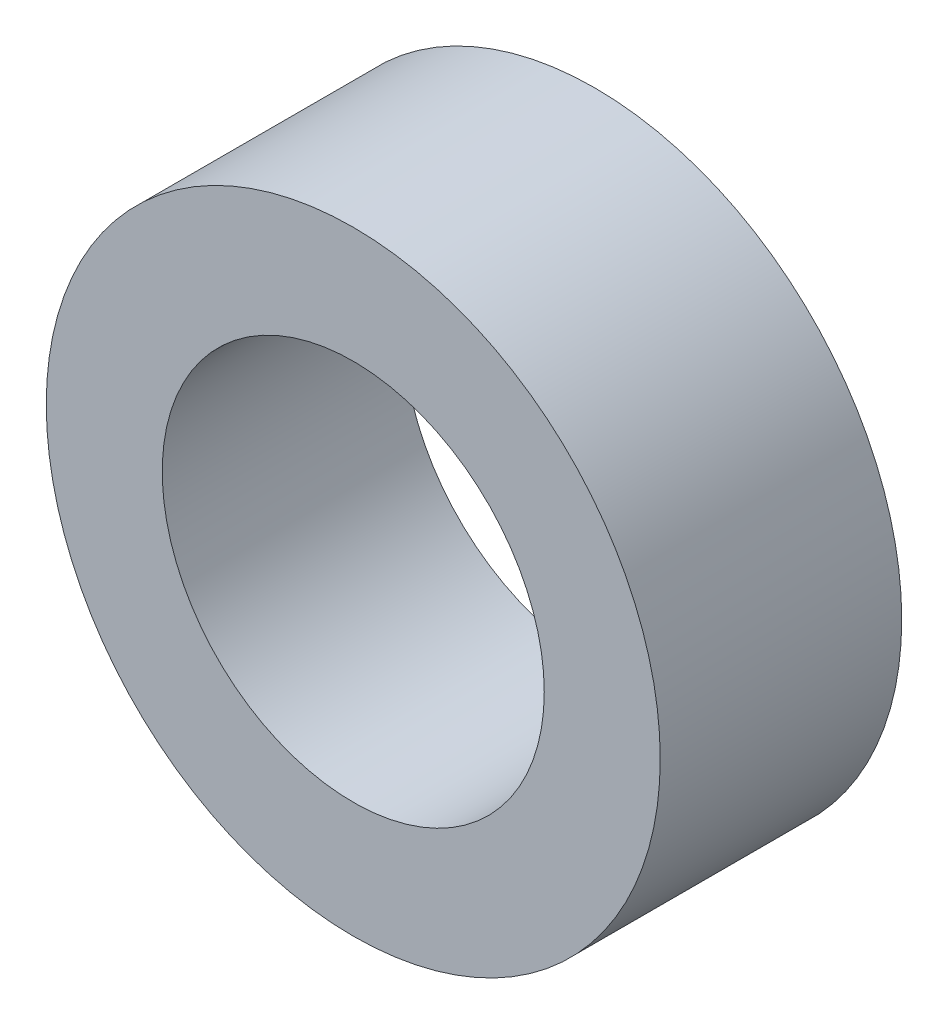
SolidWorks part; units mm, degrees
ref_plane "Alzado" through (0, 0, 0) normal (0, 0, 1) x (1, 0, 0)
ref_plane "Planta" through (0, 0, 0) normal (0, 1, 0) x (1, 0, 0)
ref_plane "Vista lateral" through (0, 0, 0) normal (1, 0, 0) x (0, 0, -1)
sketch "Croquis1" plane through (0, 0, 0) normal (0, 0, 1) x (1, 0, 0)
  circle A0 centre (0, 0) radius 22.5
  dimension "D1" = 45
extrude "Saliente-Extruir1" add sketch "Croquis1" along normal blind 17.7
sketch "Croquis2" plane through (0, 0, 17.7) normal (0, 0, 1) x (1, 0, 0)
  circle A0 centre (0, 0) radius 14
  dimension "D1" = 28
extrude "Cortar-Extruir1" cut sketch "Croquis2" against normal blind 17.7
